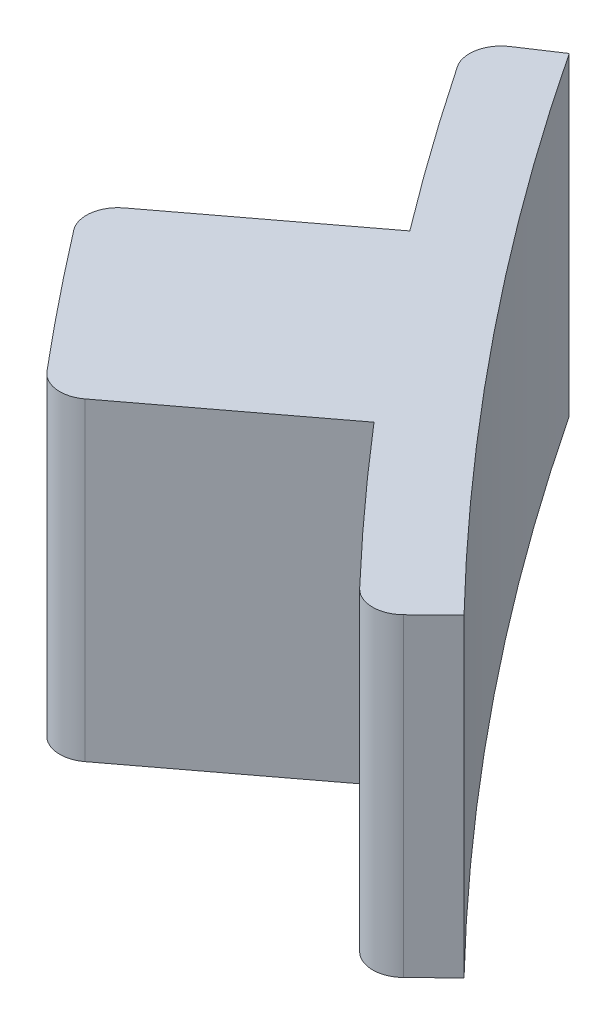
SolidWorks part; units mm, degrees
material "Plain Carbon Steel"
ref_plane "Front Plane" through (0, 0, 0) normal (0, 0, 1) x (1, 0, 0)
ref_plane "Top Plane" through (0, 0, 0) normal (0, 1, 0) x (1, 0, 0)
ref_plane "Right Plane" through (0, 0, 0) normal (1, 0, 0) x (0, 0, -1)
sketch "Sketch1" plane through (0, 0, 0) normal (0, 1, 0) x (1, 0, 0)
  line L0 (0, 0) -> (-260.052, -196.3245)
  line L1 (-248.1361, -211.1843) -> (-232.9055, -199.686)
  line L2 (0, 0) -> (-220.0651, -213.754)
  line L3 (-220.0651, -213.754) -> (-233.7293, -227.0263)
  line L4 (-220.0645, -240.2956) -> (-206.581, -226.8121)
  line L5 (-206.581, -226.8121) -> (-202.5304, -222.3648)
  line L6 (-240.048, -181.2226) -> (-244.8489, -184.8471)
  line L7 (-255.8477, -169.2967) -> (-250.8311, -165.9772)
  circle A0 centre (0, 0) radius 300.7734
  circle A1 centre (0, 0) radius 325.8379
  circle A2 centre (0, 0) radius 306.7889
  arc A3 (-260.052, -196.3245) -> (-248.1361, -211.1843) centre (0, 0) ccw
  arc A4 (-232.9055, -199.686) -> (-220.0651, -213.754) centre (0, 0) ccw
  arc A5 (-233.7293, -227.0263) -> (-220.0645, -240.2956) centre (0, 0) ccw
  arc A6 (-202.5304, -222.3648) -> (-240.048, -181.2226) centre (0, 0) cw
  arc A7 (-244.8489, -184.8471) -> (-255.8477, -169.2967) centre (0, 0) cw
  dimension "D1" = 19.05
  dimension "D2" = 19.05
  dimension "D3" = 19.05
  dimension "D4" = 19.05
extrude "Boss-Extrude1" add sketch "Sketch1" along normal blind 25.4 contours L7 A2 L0 A0 | L0 A2 L2 A0 | A2 L0 A1 L1
fillet "Fillet1" radius 2.54 4 edges at (-220.0651, 12.7, 213.754) (-255.8477, 12.7, 169.2967) (-248.1361, 12.7, 211.1843) (-260.052, 12.7, 196.3245)
